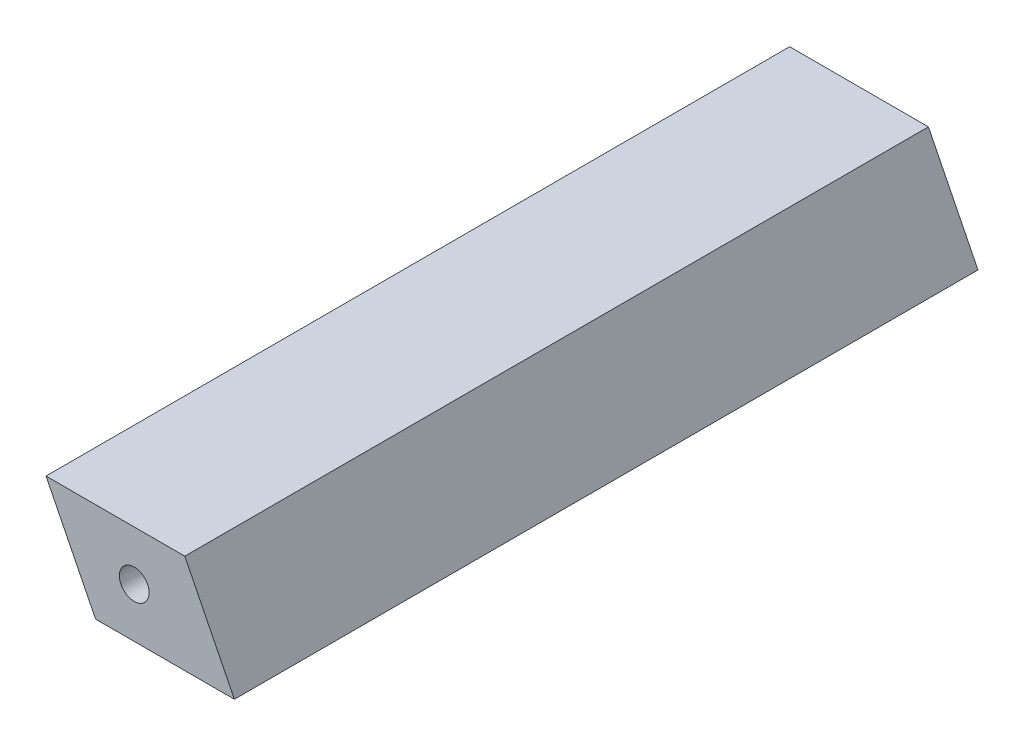
SolidWorks part; units mm, degrees
material "Teak"
ref_plane "Front Plane" through (0, 0, 0) normal (0, 0, 1) x (1, 0, 0)
ref_plane "Top Plane" through (0, 0, 0) normal (0, 1, 0) x (1, 0, 0)
ref_plane "Right Plane" through (0, 0, 0) normal (1, 0, 0) x (0, 0, -1)
sketch "Sketch1" plane through (0, 0, 0) normal (0, 0, 1) x (1, 0, 0)
  line L0 (0, 0) -> (7.112, 0)
  line L2 (4.5715, 5.08) -> (-2.5405, 5.08)
  line L3 (-2.5405, 5.08) -> (0, 0)
  line L4 (4.5715, 5.08) -> (7.112, 0)
  dimension "D1" = 5.08
  dimension "D2" = 63.43
  dimension "D3" = 7.112
extrude "Boss-Extrude1" add sketch "Sketch1" against normal blind 38.1
sketch "Sketch2" plane through (0, 0, 0) normal (0, 0, 1) x (1, 0, 0)
  line L1 (0, 0) -> (7.112, 0) construction
  line L5 (-2.5405, 5.08) -> (0, 0) construction
  circle A0 centre (1.9791, 2.54) radius 0.762
  point P4 (-1.2703, 2.54)
  dimension "D1" = 1.524
  dimension "D2" = 2.54
  dimension "D3" = 3.2494
extrude "Cut-Extrude1" cut sketch "Sketch2" against normal blind 7.62
sketch "Sketch3" plane through (0, 0, -38.1) normal (0, 0, -1) x (-1, 0, 0)
  circle A0 centre (-1.9791, 2.54) radius 0.762
  circle A1 centre (-1.9791, 2.54) radius 0.762 construction
extrude "Cut-Extrude2" cut sketch "Sketch3" against normal blind 7.62
